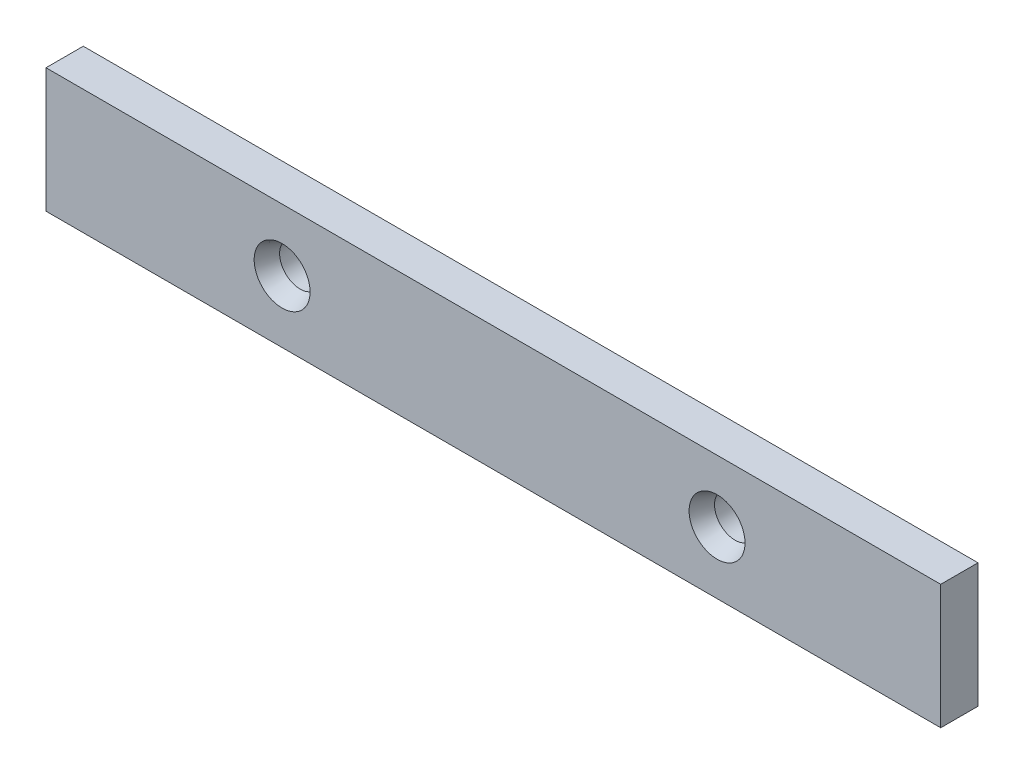
SolidWorks part; units mm, degrees
ref_plane "Front Plane" through (0, 0, 0) normal (0, 0, 1) x (1, 0, 0)
ref_plane "Top Plane" through (0, 0, 0) normal (0, 1, 0) x (1, 0, 0)
ref_plane "Right Plane" through (0, 0, 0) normal (1, 0, 0) x (0, 0, -1)
sketch "Sketch1" plane through (0, 0, 0) normal (0, 0, 1) x (1, 0, 0)
  line L1 (0, 0) -> (144, 0)
  line L2 (0, 0) -> (0, 20)
  line L3 (0, 20) -> (144, 20)
  line L4 (144, 0) -> (144, 20)
extrude "Extrude1" add sketch "Sketch1" along normal blind 6
hole_wizard "CSK for M6 Flat Head Machine Screw4" positions "3DSketch7" profile "Sketch9" countersink size "M6" standard "Ansi Metric" end condition through all
sketch3d "3DSketch7"
  line L0 (0, 0, 6) -> (144, 0, 6) construction
  line L1 (144, 0, 6) -> (144, 20, 6) construction
  point P0 (38, 10, 6)
  point P2 (108, 10, 6)
  dimension "D1" = 70
  dimension "D2" = 10
  dimension "D3" = 10
  dimension "D4" = 36
sketch "Sketch9" plane through (38, 10, 6) normal (1, 0, 0) x (0, -1, 0)
  line L0 (0, 0) -> (0, 6)
  line L1 (0, 6) -> (3.3, 6)
  line L2 (3.3, 6) -> (3.3, 2.8971)
  line L3 (3.3, 2.8971) -> (4.5, 0)
  line L5 (4.5, 0) -> (0, 0)
  line L6 (-3.3, 2.8971) -> (-4.5, 0) construction
  line L11 (0, -6.35) -> (0, 107.95) construction
  dimension "Thru Hole Dia." = 6.6
  dimension "Thru Hole Depth" = 6
  dimension "Near C'Sink Dia." = 9
  dimension "Near C'Sink Angle" = 45
